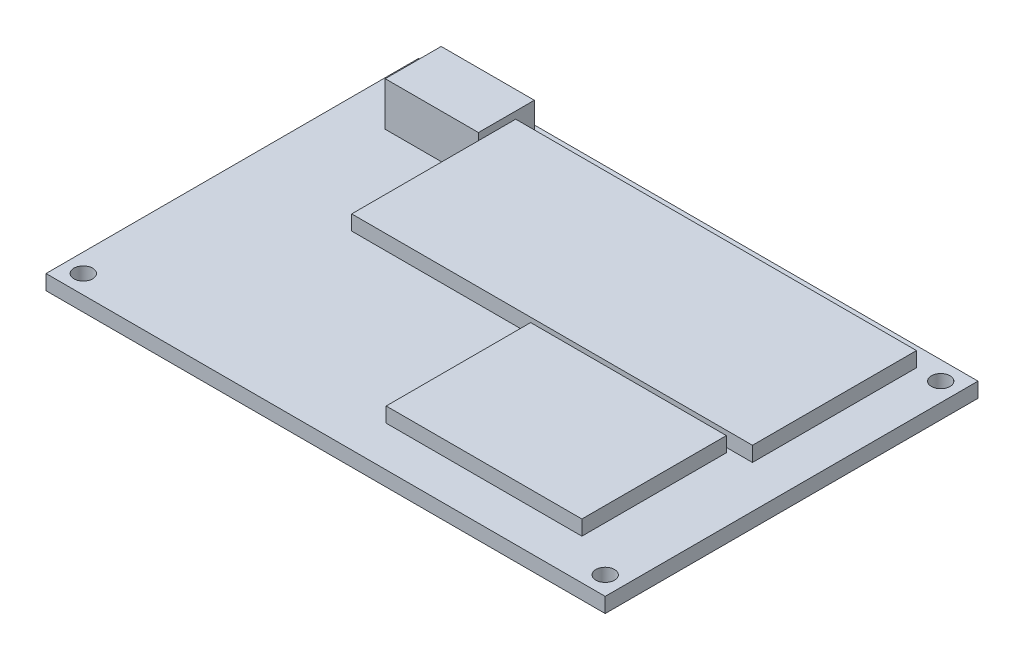
SolidWorks part; units mm, degrees
ref_plane "Front Plane" through (0, 0, 0) normal (0, 0, 1) x (1, 0, 0)
ref_plane "Top Plane" through (0, 0, 0) normal (0, 1, 0) x (1, 0, 0)
ref_plane "Right Plane" through (0, 0, 0) normal (1, 0, 0) x (0, 0, -1)
sketch "Sketch1" plane through (0, 0, 0) normal (0, 1, 0) x (1, 0, 0)
  line L0 (-30, 0) -> (30, 0) construction
  line L1 (-30, 20) -> (30, 20)
  line L2 (-30, 20) -> (-30, -20)
  line L3 (-30, -20) -> (30, -20)
  line L4 (30, 20) -> (30, -20)
  line L5 (-30, 20) -> (30, -20) construction
  line L6 (-30, -20) -> (30, 20) construction
  line L7 (0, 20) -> (0, -20) construction
  circle A0 centre (-28, 18) radius 1
  circle A1 centre (28, 18) radius 1
  circle A2 centre (28, -18) radius 1
  circle A3 centre (-28, -18) radius 1
  point P0 (0, 0)
  dimension "D3" = 2
  dimension "D1" = 60
  dimension "D2" = 40
  dimension "D4" = 56
  dimension "D5" = 36
extrude "Boss-Extrude1" add sketch "Sketch1" along normal blind 1.6
ref_plane "Plane1" through (0, 4.14, 0) normal (0, 1, 0) x (1, 0, 0)
sketch "Sketch3" plane through (0, 4.14, 0) normal (0, 1, 0) x (1, 0, 0)
  line L0 (30, 20) -> (-30, 20) construction
  line L1 (28, 15.4) -> (-15, 15.4)
  line L2 (28, 15.4) -> (28, -2.2)
  line L3 (28, -2.2) -> (-15, -2.2)
  line L4 (-15, 15.4) -> (-15, -2.2)
  line L5 (25.7, -2.7) -> (4.7, -2.7)
  line L6 (25.7, -2.7) -> (25.7, -18.2)
  line L7 (25.7, -18.2) -> (4.7, -18.2)
  line L8 (4.7, -2.7) -> (4.7, -18.2)
  line L9 (30, -20) -> (30, 20) construction
  dimension "D1" = 17.6
  dimension "D2" = 43
  dimension "D3" = 4.6
  dimension "D4" = 2
  dimension "D5" = 21
  dimension "D6" = 15.5
  dimension "D7" = 4.3
  dimension "D8" = 0.5
extrude "Boss-Extrude2" add sketch "Sketch3" along normal blind 1.6 separate body
sketch "Sketch4" plane through (0, 1.6, 0) normal (0, 1, 0) x (1, 0, 0)
  line L0 (30, 20) -> (-30, 20) construction
  line L1 (-25.2, 17.6) -> (-15.2, 17.6)
  line L2 (-25.2, 17.6) -> (-25.2, 11.6)
  line L3 (-25.2, 11.6) -> (-15.2, 11.6)
  line L4 (-15.2, 17.6) -> (-15.2, 11.6)
  line L5 (-30, 20) -> (-30, -20) construction
  dimension "D1" = 10
  dimension "D2" = 6
  dimension "D3" = 2.4
  dimension "D4" = 4.8
extrude "Boss-Extrude3" add sketch "Sketch4" along normal blind 4.7
